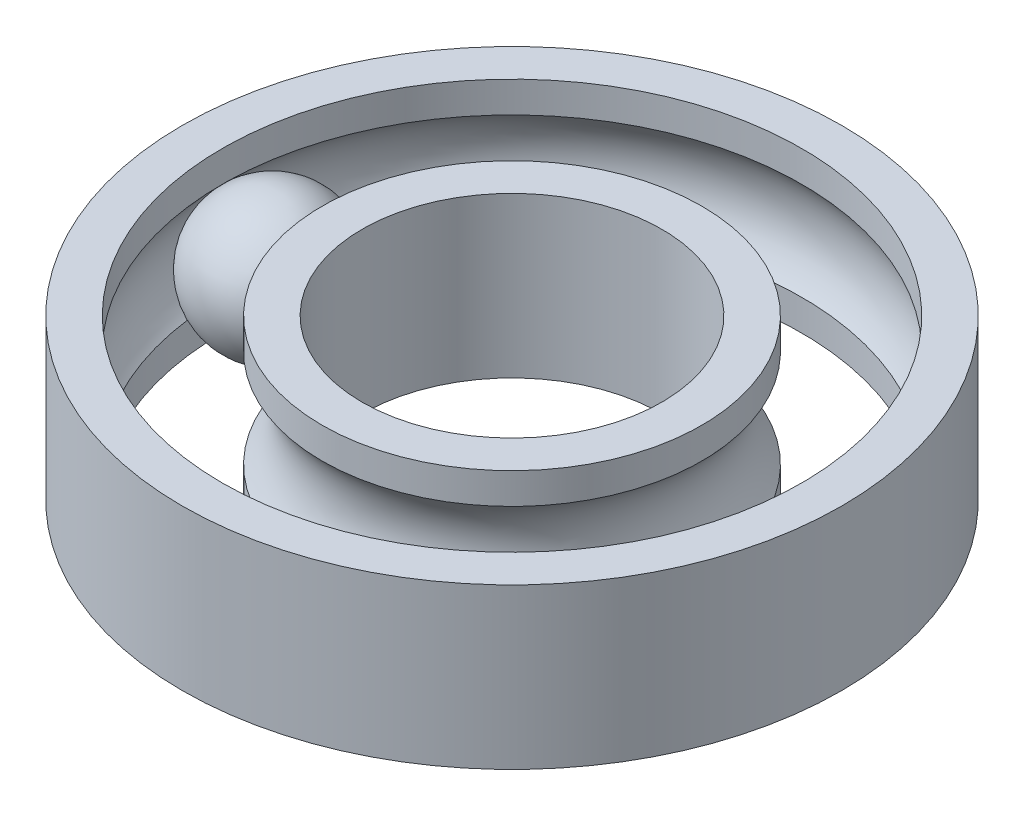
SolidWorks part; units mm, degrees
ref_plane "Front Plane" through (0, 0, 0) normal (0, 0, 1) x (1, 0, 0)
ref_plane "Top Plane" through (0, 0, 0) normal (0, 1, 0) x (1, 0, 0)
ref_plane "Right Plane" through (0, 0, 0) normal (1, 0, 0) x (0, 0, -1)
sketch "Sketch1" plane through (0, 0, 0) normal (0, 0, 1) x (1, 0, 0)
  line L0 (-41.91, -10.16) -> (-19.05, 10.16) construction
  line L1 (-41.91, -10.16) -> (-36.83, -10.16)
  line L2 (-41.91, -10.16) -> (-41.91, 10.16)
  line L3 (-41.91, 10.16) -> (-36.83, 10.16)
  line L4 (-36.83, -10.16) -> (-36.83, -6.2217)
  line L5 (-41.91, -10.16) -> (-36.83, 10.16) construction
  line L6 (-41.91, 10.16) -> (-36.83, -10.16) construction
  line L7 (-19.05, -10.16) -> (-24.13, -10.16)
  line L8 (-19.05, -10.16) -> (-19.05, 10.16)
  line L9 (-19.05, 10.16) -> (-24.13, 10.16)
  line L10 (-24.13, -10.16) -> (-24.13, -6.2217)
  line L11 (-19.05, -10.16) -> (-24.13, 10.16) construction
  line L12 (-19.05, 10.16) -> (-24.13, -10.16) construction
  line L13 (-24.13, 6.2217) -> (-24.13, 10.16)
  line L14 (-36.83, 6.2217) -> (-36.83, 10.16)
  arc A0 (-36.83, 6.2217) -> (-36.83, -6.2217) centre (-30.48, 0) ccw
  arc A1 (-24.13, -6.2217) -> (-24.13, 6.2217) centre (-30.48, 0) ccw
  point P0 (-39.37, 0)
  point P5 (-21.59, 0)
  point P14 (-19.05, 0)
  point P15 (-30.48, 0)
  point P16 (-36.83, 10.16)
  point P17 (-36.83, -10.16)
  point P21 (-36.83, 10.16)
  point P22 (-41.91, 10.16)
  point P23 (-24.13, 6.2217)
  dimension "D5" = 17.78
  dimension "D1" = 5.08
  dimension "D2" = 5.08
  dimension "D3" = 12.7
  dimension "D4" = 19.05
  dimension "D6" = 20.32
  dimension "D7" = 20.32
sketch "Sketch2" plane through (0, 0, 0) normal (0, 0, 1) x (1, 0, 0)
  line L0 (-30.48, 10.5899) -> (-30.48, -10.5899)
  arc A0 (-30.48, -8.89) -> (-30.48, 8.89) centre (-30.48, 0) ccw
  point P4 (-30.48, 0)
revolve "Revolve1" add sketch "Sketch2" angle 360 about L0
ref_axis "Axis1" through (0, 11.176, 0) along (0, -1, 0)
revolve "Revolve2" add sketch "Sketch1" angle 360 about axis through (0, 11.176, 0) along (0, -1, 0)
pattern_circular "CirPattern5" count 6 over 360 about axis through (0, 11.176, 0) along (0, -1, 0) of "Revolve1"
